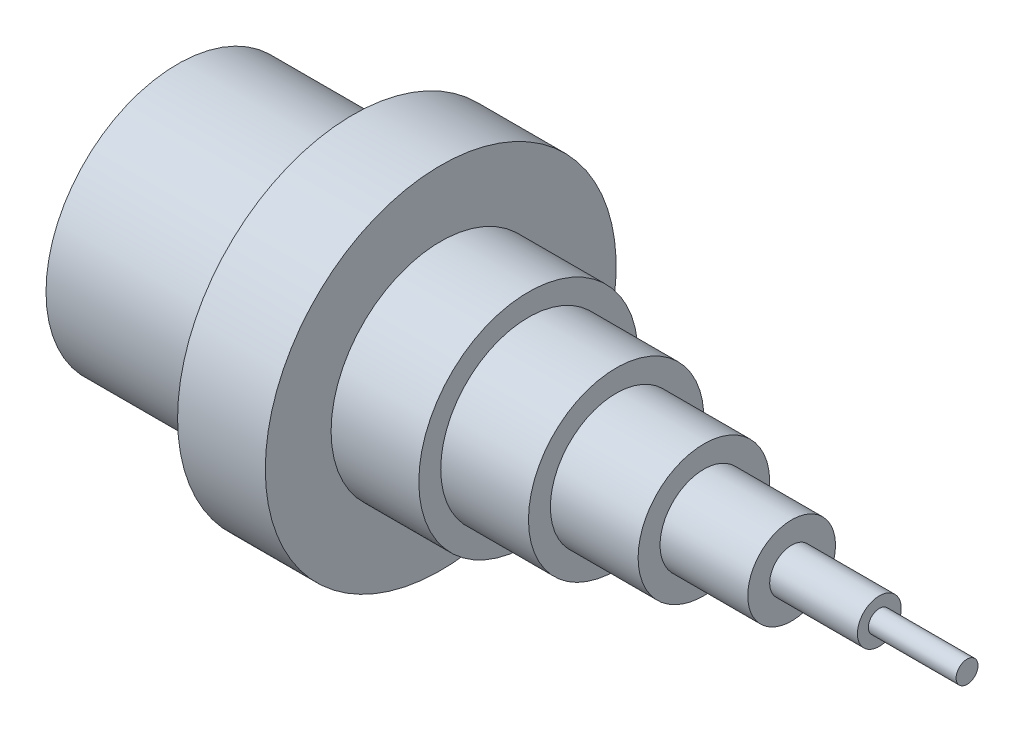
SolidWorks part; units mm, degrees
ref_plane "前基準面" through (0, 0, 0) normal (0, 0, 1) x (1, 0, 0)
ref_plane "上基準面" through (0, 0, 0) normal (0, 1, 0) x (1, 0, 0)
ref_plane "右基準面" through (0, 0, 0) normal (1, 0, 0) x (0, 0, -1)
sketch "草圖1" plane through (0, 0, 0) normal (0, 0, 1) x (1, 0, 0)
  line L1 (0, 0) -> (20, 0)
  line L2 (0, 0) -> (0, 40)
  line L3 (0, 40) -> (20, 40)
  line L4 (20, 0) -> (20, 40)
  line L5 (20, 0) -> (40, 0)
  line L6 (20, 0) -> (20, 25)
  line L7 (20, 25) -> (40, 25)
  line L8 (40, 0) -> (40, 25)
  line L9 (40, 0) -> (60, 0)
  line L10 (40, 0) -> (40, 20)
  line L11 (40, 20) -> (60, 20)
  line L12 (60, 0) -> (60, 20)
  line L13 (60, 0) -> (80, 0)
  line L14 (60, 0) -> (60, 15)
  line L15 (60, 15) -> (80, 15)
  line L16 (80, 0) -> (80, 15)
  line L17 (80, 0) -> (100, 0)
  line L18 (80, 0) -> (80, 10)
  line L19 (80, 10) -> (100, 10)
  line L20 (100, 0) -> (100, 10)
  line L21 (100, 0) -> (120, 0)
  line L22 (100, 0) -> (100, 5)
  line L23 (100, 5) -> (120, 5)
  line L24 (120, 0) -> (120, 5)
  line L25 (0, 30) -> (-40, 30)
  line L26 (0, 30) -> (0, 20)
  line L27 (0, 20) -> (-40, 20)
  line L28 (-40, 30) -> (-40, 20)
  line L29 (120, 0) -> (140, 0)
  line L30 (120, 0) -> (120, 2.5)
  line L31 (120, 2.5) -> (140, 2.5)
  line L32 (140, 0) -> (140, 2.5)
  dimension "D1" = 40
  dimension "D2" = 20
  dimension "D3" = 10
  dimension "D4" = 20
  dimension "D5" = 20
  dimension "D6" = 20
  dimension "D7" = 20
  dimension "D8" = 20
  dimension "D9" = 40
  dimension "D10" = 25
  dimension "D11" = 20
  dimension "D12" = 15
  dimension "D13" = 10
  dimension "D14" = 5
  dimension "D15" = 20
  dimension "D16" = 2.5
  dimension "D17" = 180
revolve "旋轉1" add sketch "草圖1" angle 360 about L1
